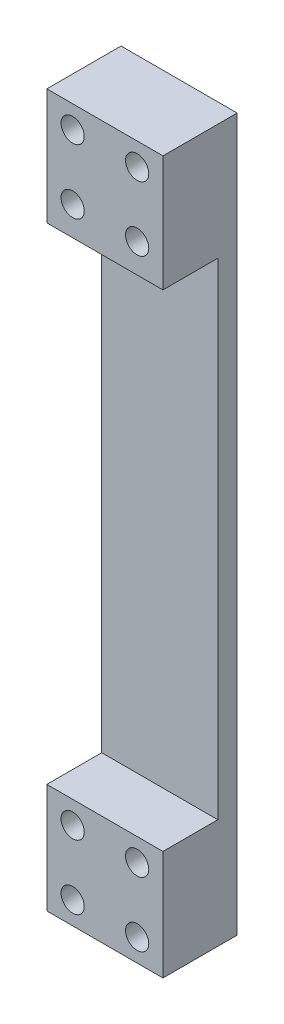
SolidWorks part; units mm, degrees
ref_plane "Front Plane" through (0, 0, 0) normal (0, 0, 1) x (1, 0, 0)
ref_plane "Top Plane" through (0, 0, 0) normal (0, 1, 0) x (1, 0, 0)
ref_plane "Right Plane" through (0, 0, 0) normal (1, 0, 0) x (0, 0, -1)
ref_plane "Plane1" through (0, 0, -0.25) normal (0, 0, 1) x (1, 0, 0)
sketch "Sketch2" plane through (0, 0, -0.25) normal (0, 0, 1) x (1, 0, 0)
  line L1 (-3.3684, -78.9574) -> (14.6316, -78.9574)
  line L2 (-3.3684, -78.9574) -> (-3.3684, 31.4426)
  line L3 (-3.3684, 31.4426) -> (14.6316, 31.4426)
  line L4 (14.6316, -78.9574) -> (14.6316, 31.4426)
extrude "Boss-Extrude1" add sketch "Sketch2" against normal blind 3
sketch "Sketch3" plane through (0, 0, -0.25) normal (0, 0, 1) x (1, 0, 0)
  line L0 (-3.3684, 31.4426) -> (14.6316, 31.4426) construction
  line L1 (14.6316, 31.4426) -> (14.6316, 13.4426) construction
  line L2 (14.6316, 13.4426) -> (-3.3684, 13.4426) construction
  line L3 (-3.3684, 13.4426) -> (-3.3684, 31.4426) construction
  line L4 (-3.3684, -61.9574) -> (14.6316, -61.9574) construction
  line L5 (14.6316, -61.9574) -> (14.6316, -79.9574) construction
  line L7 (-3.3684, -79.9574) -> (-3.3684, -61.9574) construction
  line L8 (-3.3684, 31.4426) -> (14.6316, 31.4426)
  line L9 (14.6316, 31.4426) -> (14.6316, 13.4426)
  line L10 (14.6316, 13.4426) -> (-3.3684, 13.4426)
  line L11 (-3.3684, 13.4426) -> (-3.3684, 31.4426)
  line L12 (-3.3684, -61.9574) -> (14.6316, -61.9574)
  line L13 (14.6316, -61.9574) -> (14.6316, -78.9574)
  line L15 (-3.3684, -78.9574) -> (-3.3684, -61.9574)
  line L16 (-3.3684, -78.9574) -> (14.6316, -78.9574) construction
  line L17 (-3.3684, -78.9574) -> (14.6316, -78.9574)
extrude "Boss-Extrude2" add sketch "Sketch3" along normal up to surface (8.5055 mm away)
sketch "Sketch4" plane through (0, 0, 8.2555) normal (0, 0, 1) x (1, 0, 0)
  point P0 (0.6316, -65.4574)
  point P3 (0.6316, -75.4574)
  point P6 (10.6316, -75.4574)
  point P9 (10.6316, -65.4574)
  point P12 (0.6316, 17.9426)
  point P15 (10.6316, 17.9426)
  point P18 (10.6316, 27.9426)
  point P21 (0.6316, 27.9426)
hole_wizard "M3 Clearance Hole1" positions "Sketch4" profile "Sketch5" hole size "M3" standard "ANSI Metric" end condition through all
sketch "Sketch5" plane through (0.6316, -65.4574, 8.2555) normal (1, 0, 0) x (0, -1, 0)
  line L0 (0, 0) -> (0, 11.5055)
  line L1 (0, 11.5055) -> (1.8, 11.5055)
  line L2 (1.8, 11.5055) -> (1.8, 0)
  line L5 (1.8, 0) -> (0, 0)
  line L11 (0, -6.35) -> (0, 107.95) construction
  dimension "Thru Hole Dia." = 3.6
  dimension "Thru Hole Depth" = 11.5055
